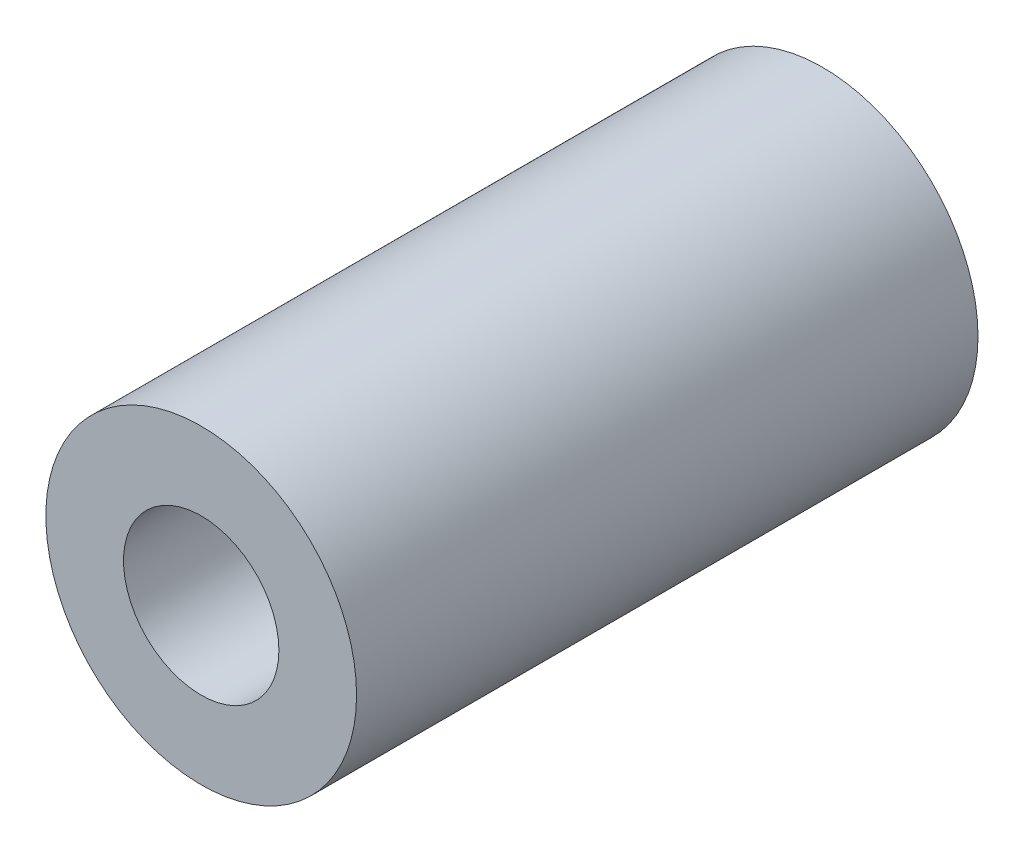
SolidWorks part; units mm, degrees
ref_plane "Front Plane" through (0, 0, 0) normal (0, 0, 1) x (1, 0, 0)
ref_plane "Top Plane" through (0, 0, 0) normal (0, 1, 0) x (1, 0, 0)
ref_plane "Right Plane" through (0, 0, 0) normal (1, 0, 0) x (0, 0, -1)
sketch "Sketch1" plane through (0, 0, 0) normal (0, 0, 1) x (1, 0, 0)
  circle A0 centre (4, 4) radius 4
  circle A1 centre (4, 4) radius 2
  dimension "D1" = 4
  dimension "D2" = 8
extrude "Profile" add sketch "Sketch1" along normal blind 16
equation "\"Profile_Depth\"= 16mm"
equation "\"D1@Profile\" = \"Profile_Depth\""
equation "\"Profile_Sketch_1\"= 4mm"
equation "\"D1@Sketch1\" = \"Profile_Sketch_1\""
equation "\"Profile_Sketch_2\"= 8mm"
equation "\"D2@Sketch1\" = \"Profile_Sketch_2\""
equation "\"EnvelopeWidth\"= 8mm"
equation "\"EnvelopeHeight\"= 8mm"
